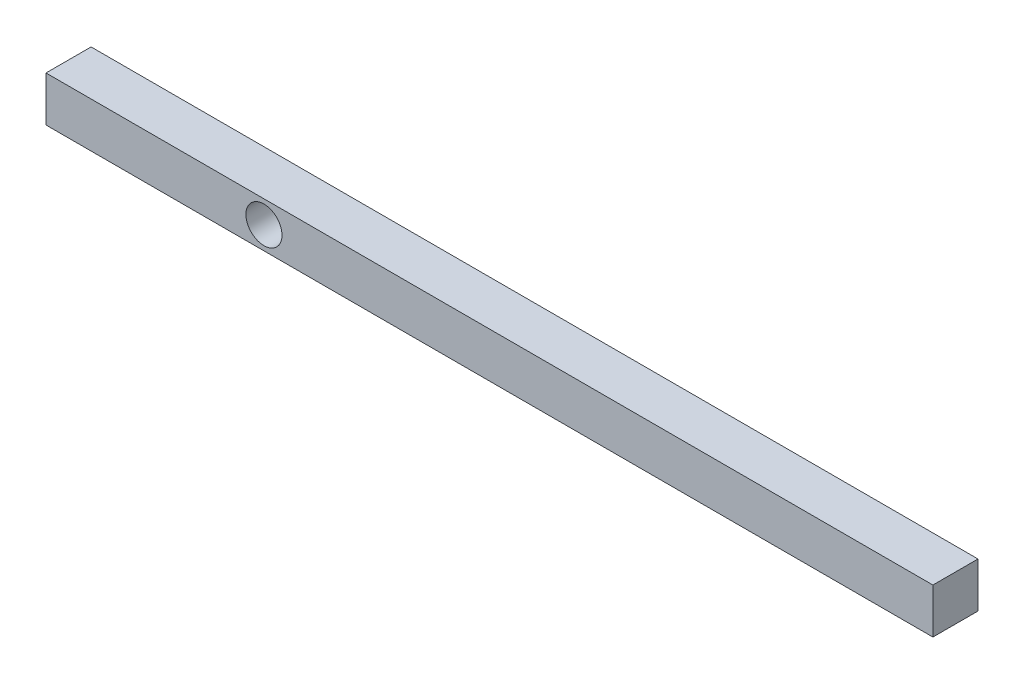
SolidWorks part; units mm, degrees
material "Plain Carbon Steel"
ref_plane "Front Plane" through (0, 0, 0) normal (0, 0, 1) x (1, 0, 0)
ref_plane "Top Plane" through (0, 0, 0) normal (0, 1, 0) x (1, 0, 0)
ref_plane "Right Plane" through (0, 0, 0) normal (1, 0, 0) x (0, 0, -1)
sketch "Sketch1" plane through (0, 0, 0) normal (0, 0, 1) x (1, 0, 0)
  line L0 (-58, -6) -> (178, -6)
  line L1 (178, -6) -> (178, 6)
  line L2 (178, 6) -> (-58, 6)
  line L3 (-58, 6) -> (-58, -6)
  dimension "D1" = 236
  dimension "D2" = 12
  dimension "D3" = 58
  dimension "D4" = 6
extrude "Boss-Extrude1" add sketch "Sketch1" along normal mid plane 12
sketch "Sketch2" plane through (0, 0, 0) normal (0, 0, 1) x (1, 0, 0)
  circle A0 centre (0, 0) radius 4.8
  dimension "D1" = 9.6
extrude "Cut-Extrude1" cut sketch "Sketch2" against normal mid plane 24
